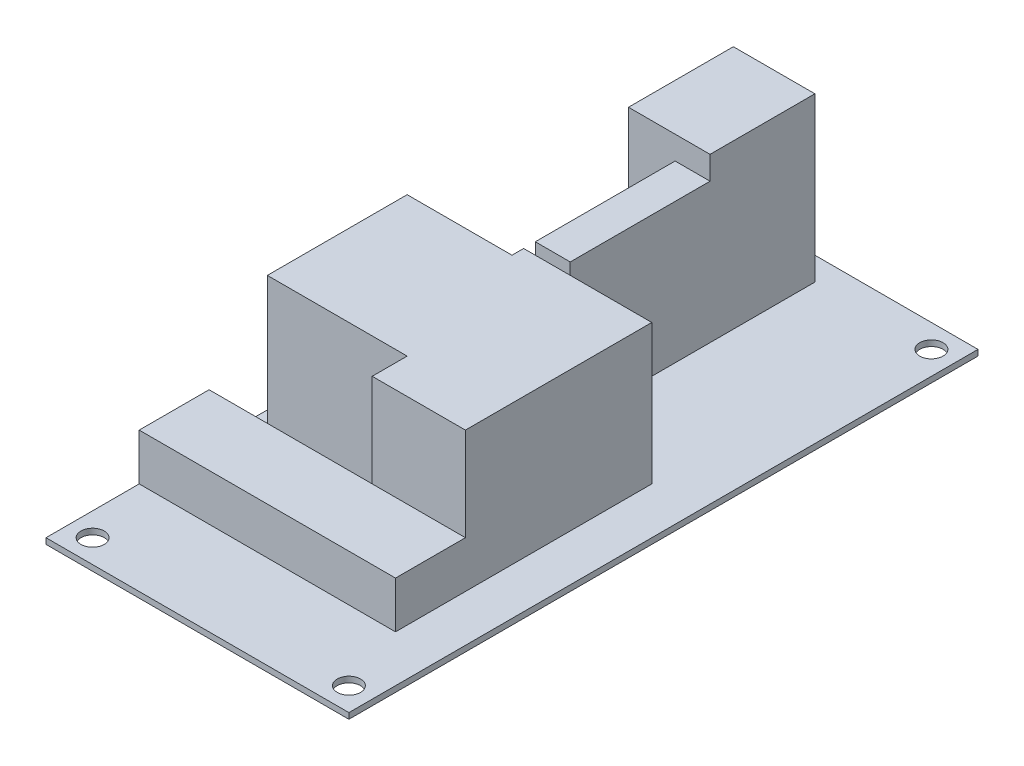
SolidWorks part; units mm, degrees
ref_plane "Front Plane" through (0, 0, 0) normal (0, 0, 1) x (1, 0, 0)
ref_plane "Top Plane" through (0, 0, 0) normal (0, 1, 0) x (1, 0, 0)
ref_plane "Right Plane" through (0, 0, 0) normal (1, 0, 0) x (0, 0, -1)
sketch "Sketch1" plane through (0, 0, 0) normal (0, 1, 0) x (1, 0, 0)
  line L1 (-20.6375, 42.8625) -> (20.6375, 42.8625)
  line L2 (-20.6375, 42.8625) -> (-20.6375, -42.8625)
  line L3 (-20.6375, -42.8625) -> (20.6375, -42.8625)
  line L4 (20.6375, 42.8625) -> (20.6375, -42.8625)
  line L5 (-20.6375, 42.8625) -> (20.6375, -42.8625) construction
  line L6 (-20.6375, -42.8625) -> (20.6375, 42.8625) construction
  point P0 (0, 0)
  dimension "D1" = 85.725
  dimension "D2" = 41.275
extrude "Boss-Extrude1" add sketch "Sketch1" along normal blind 0.7937
sketch "Sketch2" plane through (0, 0.7937, 0) normal (0, 1, 0) x (1, 0, 0)
  line L0 (-20.6375, 42.8625) -> (-20.6375, -42.8625) construction
  line L1 (-20.6375, -30.1625) -> (14.2875, -30.1625)
  line L2 (-20.6375, -30.1625) -> (-20.6375, -20.6375)
  line L3 (-20.6375, -20.6375) -> (14.2875, -20.6375)
  line L4 (14.2875, -30.1625) -> (14.2875, -20.6375)
  line L5 (-20.6375, -42.8625) -> (20.6375, -42.8625) construction
  dimension "D1" = 34.925
  dimension "D2" = 12.7
  dimension "D3" = 9.525
extrude "Boss-Extrude2" add sketch "Sketch2" along normal blind 6.35
sketch "Sketch3" plane through (0, 0.7937, 0) normal (0, 1, 0) x (1, 0, 0)
  line L0 (14.2875, -20.6375) -> (14.2875, 4.7625)
  line L1 (14.2875, 4.7625) -> (-3.175, 4.7625)
  line L2 (-3.175, 4.7625) -> (-3.175, 3.175)
  line L3 (-3.175, 3.175) -> (-17.4625, 3.175)
  line L4 (-17.4625, 3.175) -> (-17.4625, -15.875)
  line L5 (-17.4625, -15.875) -> (1.5875, -15.875)
  line L6 (1.5875, -15.875) -> (1.5875, -20.6375)
  line L7 (14.2875, -20.6375) -> (-20.6375, -20.6375) construction
  line L8 (1.5875, -20.6375) -> (14.2875, -20.6375)
  dimension "D1" = 17.4625
  dimension "D2" = 1.5875
  dimension "D3" = 14.2875
  dimension "D4" = 19.05
  dimension "D5" = 12.7
  dimension "D6" = 4.7625
extrude "Boss-Extrude3" add sketch "Sketch3" along normal blind 19.05
sketch "Sketch4" plane through (0, 0.7937, 0) normal (0, 1, 0) x (1, 0, 0)
  line L1 (-14.2875, 9.525) -> (-3.175, 9.525)
  line L2 (-14.2875, 9.525) -> (-14.2875, 20.6375)
  line L3 (-14.2875, 20.6375) -> (-3.175, 20.6375)
  line L4 (-3.175, 9.525) -> (-3.175, 20.6375)
  line L5 (-3.175, 4.7625) -> (-3.175, 3.175) construction
  line L6 (-3.175, 3.175) -> (-17.4625, 3.175) construction
  dimension "D1" = 6.35
  dimension "D2" = 11.1125
  dimension "D3" = 11.1125
extrude "Boss-Extrude4" add sketch "Sketch4" along normal blind 6.35
sketch "Sketch5" plane through (0, 7.1437, 0) normal (0, 1, 0) x (1, 0, 0)
  line L0 (-3.175, 20.6375) -> (-14.2875, 20.6375) construction
  line L1 (-14.2875, 20.6375) -> (-14.2875, 9.525) construction
  circle A0 centre (-8.7313, 15.0812) radius 2.3813
  point P5 (-8.7313, 20.6375)
  point P9 (-14.2875, 15.0812)
  dimension "D1" = 4.7625
extrude "Boss-Extrude5" add sketch "Sketch5" along normal blind 3.175
sketch "Sketch6" plane through (0, 0.7937, 0) normal (0, 1, 0) x (1, 0, 0)
  line L0 (-3.175, 9.525) -> (-3.175, 20.6375) construction
  line L1 (-3.175, 6.35) -> (1.5875, 6.35)
  line L2 (-3.175, 6.35) -> (-3.175, 25.4)
  line L3 (-3.175, 25.4) -> (1.5875, 25.4)
  line L4 (1.5875, 6.35) -> (1.5875, 25.4)
  line L5 (14.2875, 4.7625) -> (-3.175, 4.7625) construction
  dimension "D1" = 1.5875
  dimension "D2" = 4.7625
  dimension "D3" = 19.05
extrude "Boss-Extrude6" add sketch "Sketch6" along normal blind 19.05
sketch "Sketch7" plane through (0, 0.7937, 0) normal (0, 1, 0) x (1, 0, 0)
  line L0 (-20.6375, 42.8625) -> (-20.6375, -20.6375) construction
  line L1 (-9.525, 25.4) -> (1.5875, 25.4)
  line L2 (-9.525, 25.4) -> (-9.525, 39.6875)
  line L3 (-9.525, 39.6875) -> (1.5875, 39.6875)
  line L4 (1.5875, 25.4) -> (1.5875, 39.6875)
  line L5 (20.6375, 42.8625) -> (-20.6375, 42.8625) construction
  line L6 (1.5875, 6.35) -> (1.5875, 25.4) construction
  dimension "D1" = 11.1125
  dimension "D2" = 3.175
  dimension "D3" = 14.2875
extrude "Boss-Extrude7" add sketch "Sketch7" along normal blind 22.225
sketch "Sketch8" plane through (0, 0.7937, 0) normal (0, 1, 0) x (1, 0, 0)
  line L0 (-20.6375, 42.8625) -> (-20.6375, -20.6375) construction
  line L1 (-17.4625, -39.6875) -> (17.4625, -39.6875) construction
  line L2 (-17.4625, -39.6875) -> (-17.4625, 39.6875) construction
  line L3 (-17.4625, 39.6875) -> (17.4625, 39.6875) construction
  line L4 (17.4625, -39.6875) -> (17.4625, 39.6875) construction
  line L5 (20.6375, -42.8625) -> (20.6375, 42.8625) construction
  line L6 (20.6375, 42.8625) -> (-20.6375, 42.8625) construction
  line L7 (-20.6375, -42.8625) -> (20.6375, -42.8625) construction
  circle A3 centre (-17.4625, 39.6875) radius 1.5875
  circle A4 centre (17.4625, 39.6875) radius 1.5875
  circle A5 centre (-17.4625, -39.6875) radius 1.5875
  circle A6 centre (17.4625, -39.6875) radius 1.5875
  dimension "D5" = 3.175
  dimension "D1" = 3.175
  dimension "D2" = 3.175
  dimension "D3" = 3.175
  dimension "D4" = 3.175
extrude "Cut-Extrude1" cut sketch "Sketch8" against normal through all
